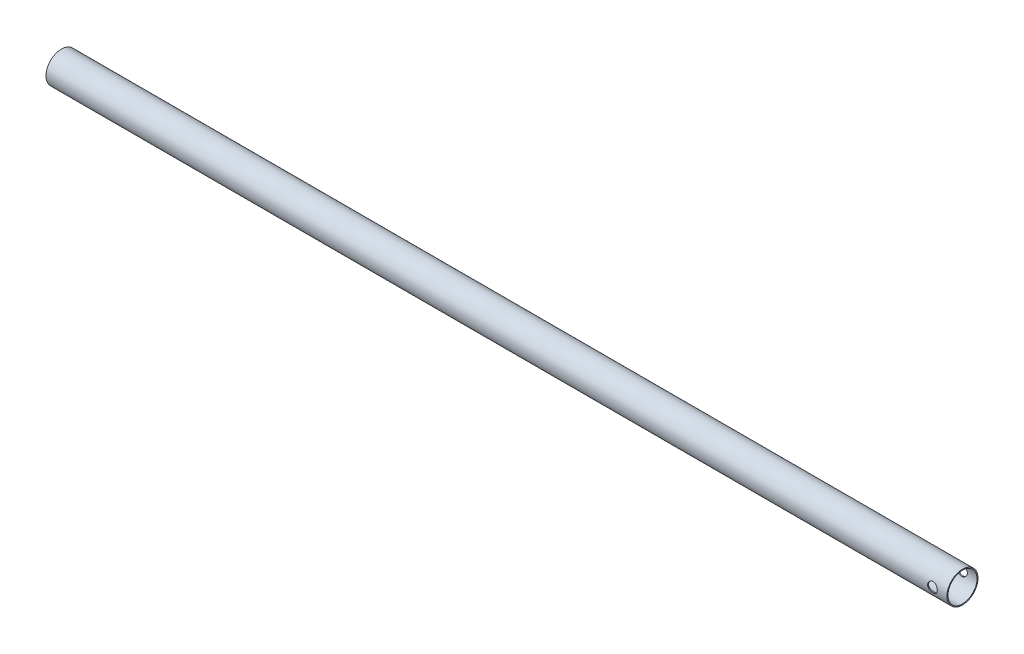
SolidWorks part; units mm, degrees
ref_plane "Front Plane" through (0, 0, 0) normal (0, 0, 1) x (1, 0, 0)
ref_plane "Top Plane" through (0, 0, 0) normal (0, 1, 0) x (1, 0, 0)
ref_plane "Right Plane" through (0, 0, 0) normal (1, 0, 0) x (0, 0, -1)
sketch "Sketch2" plane through (0, 0, 0) normal (1, 0, 0) x (0, 0, -1)
  circle A0 centre (0, 0) radius 16
  dimension "D1" = 32
extrude "Extrude-Thin1" add sketch "Sketch2" against normal blind 929 thin thin type one direction reverse wall 1
sketch "Sketch4" plane through (0, 0, 0) normal (0, 0, 1) x (1, 0, 0)
  line L0 (0, 0) -> (-929, 0) construction
  line L1 (-929, 16) -> (-929, -16) construction
  line L2 (0, -16) -> (0, 16) construction
  circle A0 centre (-15, 0) radius 5
  dimension "D1" = 10
  dimension "D2" = 15
extrude "Cut-Extrude1" cut sketch "Sketch4" against normal mid plane 40
